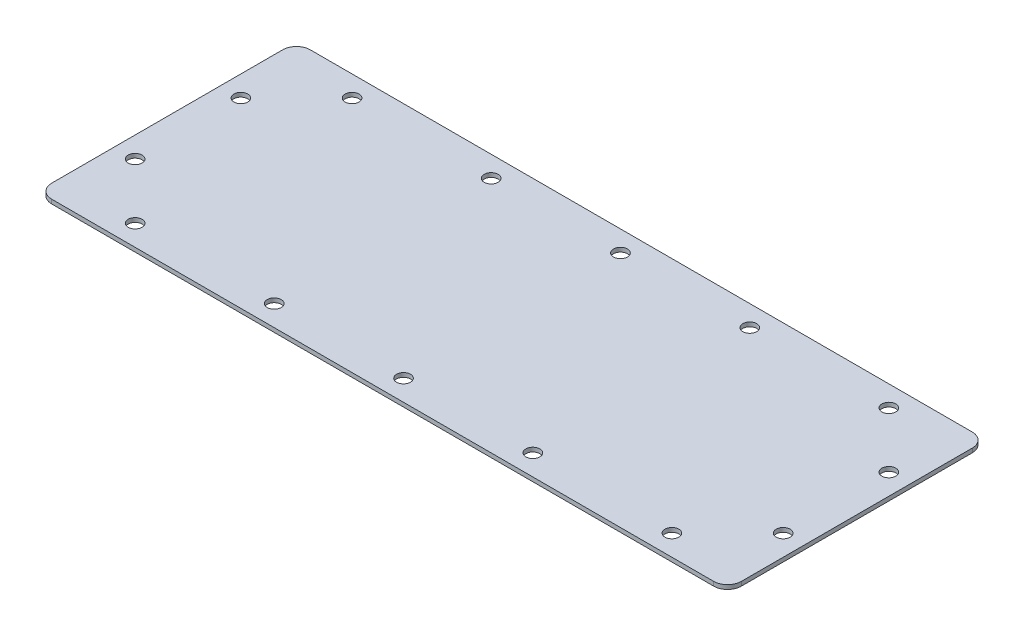
SolidWorks part; units mm, degrees
material "5052-H32"
ref_plane "Front Plane" through (0, 0, 0) normal (0, 0, 1) x (1, 0, 0)
ref_plane "Top Plane" through (0, 0, 0) normal (0, 1, 0) x (1, 0, 0)
ref_plane "Right Plane" through (0, 0, 0) normal (1, 0, 0) x (0, 0, -1)
sketch "Sketch1" plane through (0, 0, 0) normal (0, 1, 0) x (1, 0, 0)
  line L0 (-248, 0) -> (248, 0) construction
  line L1 (-238, 93) -> (238, 93)
  line L2 (-248, 83) -> (-248, -83)
  line L3 (-238, -93) -> (238, -93)
  line L4 (248, 83) -> (248, -83)
  line L5 (-248, 93) -> (248, -93) construction
  line L6 (-248, -93) -> (248, 93) construction
  line L7 (-233, 78) -> (233, 78) construction
  line L8 (-233, 78) -> (-233, -78) construction
  line L9 (-233, -78) -> (233, -78) construction
  line L10 (233, 78) -> (233, -78) construction
  line L11 (-233, 78) -> (233, -78) construction
  line L12 (-233, -78) -> (233, 78) construction
  arc A0 (238, 93) -> (248, 83) centre (238, 83) cw
  arc A1 (238, -93) -> (248, -83) centre (238, -83) ccw
  arc A2 (-248, -83) -> (-238, -93) centre (-238, -83) ccw
  arc A3 (-238, 93) -> (-248, 83) centre (-238, 83) ccw
  circle A4 centre (-193, 78) radius 5
  circle A5 centre (-93, 78) radius 5
  circle A6 centre (0, 78) radius 5
  circle A7 centre (-233, 38) radius 5
  circle A8 centre (93, 78) radius 5
  circle A9 centre (193, 78) radius 5
  circle A10 centre (233, 38) radius 5
  circle A11 centre (233, -38) radius 5
  circle A12 centre (193, -78) radius 5
  circle A13 centre (93, -78) radius 5
  circle A14 centre (0, -78) radius 5
  circle A15 centre (-93, -78) radius 5
  circle A16 centre (-193, -78) radius 5
  circle A17 centre (-233, -38) radius 5
  point P4 (0, 0)
  point P23 (0, 0)
  dimension "D3" = 10
  dimension "D6" = 10
  dimension "D1" = 496
  dimension "D2" = 186
  dimension "D4" = 15
  dimension "D5" = 15
  dimension "D7" = 40
  dimension "D8" = 40
  dimension "D9" = 40
  dimension "D10" = 100
  dimension "D11" = 100
extrude "Boss-Extrude1" add sketch "Sketch1" along normal blind 3
